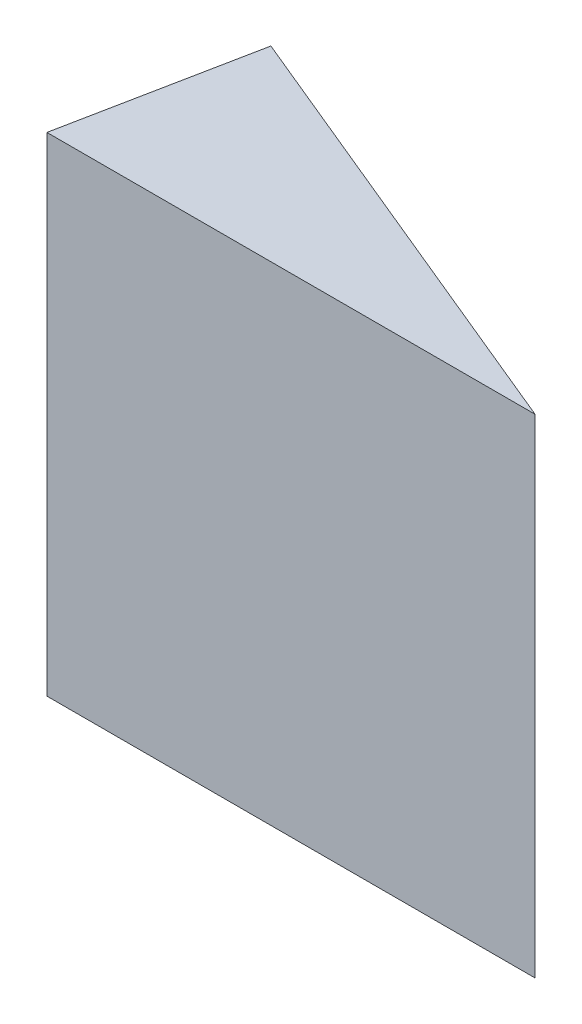
SolidWorks part; units mm, degrees
material "AISI 316 Annealed Stainless Steel Bar (SS)"
ref_plane "Front Plane" through (0, 0, 0) normal (0, 0, 1) x (1, 0, 0)
ref_plane "Top Plane" through (0, 0, 0) normal (0, 1, 0) x (1, 0, 0)
ref_plane "Right Plane" through (0, 0, 0) normal (1, 0, 0) x (0, 0, -1)
sketch "Sketch1" plane through (0, 0, 0) normal (0, 1, 0) x (1, 0, 0)
  line L0 (12.7, -13.0829) -> (-10.7665, -3.3628)
  line L5 (-12.7, -13.0829) -> (12.7, -13.0829)
  line L6 (-12.7, -13.0829) -> (-10.7665, -3.3628)
  point P0 (0, 0)
  point P1 (0, 0)
  dimension "D1" = 25.4
  dimension "D2" = 22.5
  dimension "D3" = 25.4
extrude "Boss-Extrude1" add sketch "Sketch1" along normal mid plane 25.4
